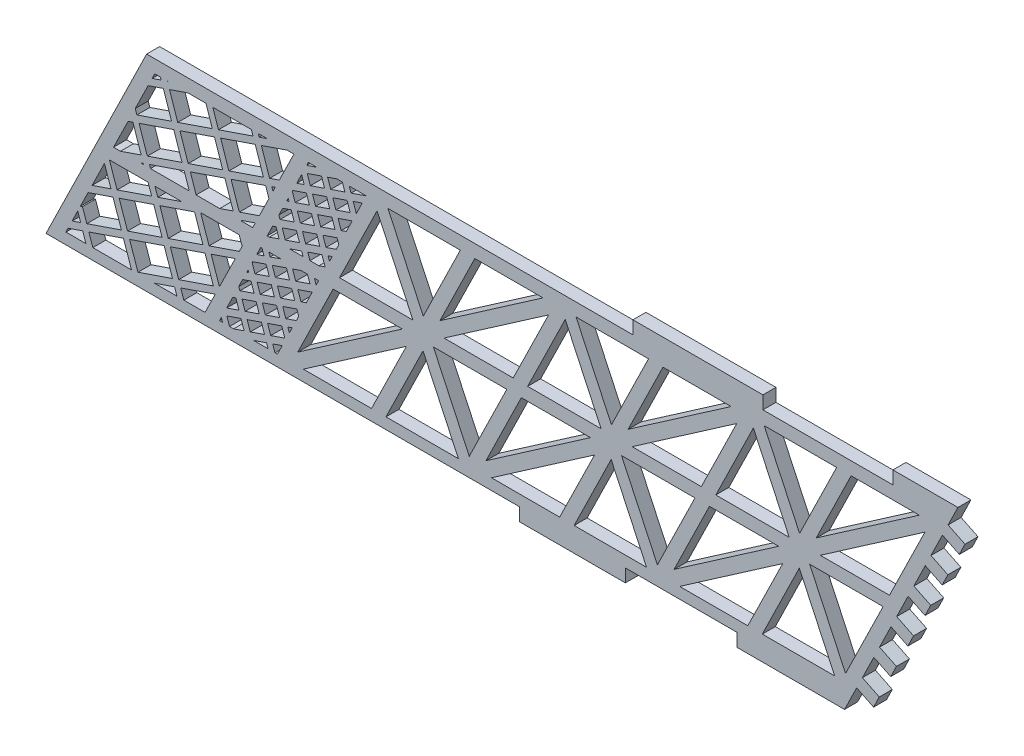
SolidWorks part; units mm, degrees
ref_plane "Front Plane" through (0, 0, 0) normal (0, 0, 1) x (1, 0, 0)
ref_plane "Top Plane" through (0, 0, 0) normal (0, 1, 0) x (1, 0, 0)
ref_plane "Right Plane" through (0, 0, 0) normal (1, 0, 0) x (0, 0, -1)
sketch "Sketch1" plane through (0, 0, 0) normal (0, 0, 1) x (1, 0, 0)
  line L3478 (51.1715, 290.0859) -> (43.1947, 287.3513)
  line L3479 (43.1947, 287.3513) -> (41.8771, 291.1947)
  line L3480 (41.8771, 291.1947) -> (50.7914, 291.1947)
  line L3481 (50.7914, 291.1947) -> (51.1715, 290.0859)
  line L3482 (51.658, 288.6669) -> (43.6811, 285.9324)
  line L3483 (43.6811, 285.9324) -> (45.6023, 280.3279)
  line L3484 (45.6023, 280.3279) -> (53.5792, 283.0625)
  line L3485 (53.5792, 283.0625) -> (51.658, 288.6669)
  line L3486 (55.4846, 282.13) -> (56.3022, 282.4102)
  line L3487 (56.3022, 282.4102) -> (55.7649, 281.3124)
  line L3488 (55.7649, 281.3124) -> (55.4846, 282.13)
  line L3489 (54.9982, 283.5489) -> (57.2347, 284.3156)
  line L3490 (57.2347, 284.3156) -> (60.6014, 291.1947)
  line L3491 (60.6014, 291.1947) -> (59.0316, 291.1947)
  line L3492 (59.0316, 291.1947) -> (53.0769, 289.1534)
  line L3493 (53.0769, 289.1534) -> (54.9982, 283.5489)
  line L3494 (52.5905, 290.5723) -> (54.406, 291.1947)
  line L3495 (54.406, 291.1947) -> (52.3771, 291.1947)
  line L3496 (52.3771, 291.1947) -> (52.5905, 290.5723)
  line L3497 (46.0888, 278.909) -> (48.01, 273.3046)
  line L3498 (48.01, 273.3046) -> (52.6189, 274.8845)
  line L3499 (52.6189, 274.8845) -> (54.8323, 279.407)
  line L3500 (54.8323, 279.407) -> (54.0656, 281.6436)
  line L3501 (54.0656, 281.6436) -> (46.0888, 278.909)
  line L3502 (22.1987, 256.6075) -> (30.1756, 259.342)
  line L3503 (30.1756, 259.342) -> (28.2543, 264.9465)
  line L3504 (28.2543, 264.9465) -> (20.2774, 262.2119)
  line L3505 (20.2774, 262.2119) -> (22.1987, 256.6075)
  line L3506 (19.791, 263.6308) -> (27.7679, 266.3654)
  line L3507 (27.7679, 266.3654) -> (26.9509, 268.7488)
  line L3508 (26.9509, 268.7488) -> (18.0365, 268.7488)
  line L3509 (18.0365, 268.7488) -> (19.791, 263.6308)
  line L3510 (18.3721, 263.1444) -> (14.0328, 261.6569)
  line L3511 (14.0328, 261.6569) -> (16.8845, 267.4837)
  line L3512 (16.8845, 267.4837) -> (18.3721, 263.1444)
  line L3513 (18.8585, 261.7255) -> (20.7797, 256.121)
  line L3514 (20.7797, 256.121) -> (12.8029, 253.3865)
  line L3515 (12.8029, 253.3865) -> (11.8034, 256.302)
  line L3516 (11.8034, 256.302) -> (11.3331, 256.1408)
  line L3517 (11.3331, 256.1408) -> (13.1003, 259.7515)
  line L3518 (13.1003, 259.7515) -> (18.8585, 261.7255)
  line L3519 (13.2893, 251.9675) -> (14.2028, 249.3028)
  line L3520 (14.2028, 249.3028) -> (23.1171, 249.3028)
  line L3521 (23.1171, 249.3028) -> (21.2662, 254.7021)
  line L3522 (21.2662, 254.7021) -> (13.2893, 251.9675)
  line L3523 (24.6064, 249.5841) -> (32.5833, 252.3186)
  line L3524 (32.5833, 252.3186) -> (30.662, 257.9231)
  line L3525 (30.662, 257.9231) -> (22.6851, 255.1885)
  line L3526 (22.6851, 255.1885) -> (24.6064, 249.5841)
  line L3527 (25.8466, 271.9698) -> (25.2017, 271.7488)
  line L3528 (25.2017, 271.7488) -> (25.9224, 271.7488)
  line L3529 (25.9224, 271.7488) -> (25.8466, 271.9698)
  line L3530 (23.439, 278.9932) -> (22.3317, 278.6137)
  line L3531 (22.3317, 278.6137) -> (18.9719, 271.7488)
  line L3532 (18.9719, 271.7488) -> (20.5761, 271.7488)
  line L3533 (20.5761, 271.7488) -> (25.3602, 273.3888)
  line L3534 (25.3602, 273.3888) -> (23.439, 278.9932)
  line L3535 (26.7792, 273.8752) -> (34.7876, 276.6206)
  line L3536 (34.7876, 276.6206) -> (32.8663, 282.225)
  line L3537 (32.8663, 282.225) -> (24.8579, 279.4797)
  line L3538 (24.8579, 279.4797) -> (26.7792, 273.8752)
  line L3539 (27.5081, 271.7488) -> (36.4577, 271.7488)
  line L3540 (36.4577, 271.7488) -> (35.274, 275.2016)
  line L3541 (35.274, 275.2016) -> (27.2656, 272.4563)
  line L3542 (27.2656, 272.4563) -> (27.5081, 271.7488)
  line L3543 (29.1868, 266.8518) -> (34.7204, 268.7488)
  line L3544 (34.7204, 268.7488) -> (28.5365, 268.7488)
  line L3545 (28.5365, 268.7488) -> (29.1868, 266.8518)
  line L3546 (31.5945, 259.8284) -> (39.6029, 262.5738)
  line L3547 (39.6029, 262.5738) -> (37.6817, 268.1782)
  line L3548 (37.6817, 268.1782) -> (29.6733, 265.4329)
  line L3549 (29.6733, 265.4329) -> (31.5945, 259.8284)
  line L3550 (34.0022, 252.805) -> (42.0106, 255.5504)
  line L3551 (42.0106, 255.5504) -> (40.0893, 261.1548)
  line L3552 (40.0893, 261.1548) -> (32.0809, 258.4095)
  line L3553 (32.0809, 258.4095) -> (34.0022, 252.805)
  line L3554 (24.3715, 280.8986) -> (32.3799, 283.644)
  line L3555 (32.3799, 283.644) -> (30.4586, 289.2484)
  line L3556 (30.4586, 289.2484) -> (26.9474, 288.0447)
  line L3557 (26.9474, 288.0447) -> (23.9919, 282.0059)
  line L3558 (23.9919, 282.0059) -> (24.3715, 280.8986)
  line L3559 (44.6698, 278.4226) -> (36.6929, 275.688)
  line L3560 (36.6929, 275.688) -> (38.0434, 271.7488)
  line L3561 (38.0434, 271.7488) -> (43.4716, 271.7488)
  line L3562 (43.4716, 271.7488) -> (46.5911, 272.8181)
  line L3563 (46.5911, 272.8181) -> (44.6698, 278.4226)
  line L3564 (42.2621, 285.446) -> (34.2853, 282.7114)
  line L3565 (34.2853, 282.7114) -> (36.2065, 277.107)
  line L3566 (36.2065, 277.107) -> (44.1834, 279.8415)
  line L3567 (44.1834, 279.8415) -> (42.2621, 285.446)
  line L3568 (41.7757, 286.8649) -> (33.7988, 284.1304)
  line L3569 (33.7988, 284.1304) -> (31.8776, 289.7348)
  line L3570 (31.8776, 289.7348) -> (36.1361, 291.1947)
  line L3571 (36.1361, 291.1947) -> (40.2914, 291.1947)
  line L3572 (40.2914, 291.1947) -> (41.7757, 286.8649)
  line L3573 (48.5434, 271.7488) -> (51.0843, 271.7488)
  line L3574 (51.0843, 271.7488) -> (51.6864, 272.9792)
  line L3575 (51.6864, 272.9792) -> (48.4964, 271.8856)
  line L3576 (48.4964, 271.8856) -> (48.5434, 271.7488)
  line L3577 (49.5718, 268.7488) -> (49.616, 268.7488)
  line L3578 (49.616, 268.7488) -> (49.59, 268.6956)
  line L3579 (49.59, 268.6956) -> (49.5718, 268.7488)
  line L3580 (29.9722, 290.6674) -> (27.8799, 289.9501)
  line L3581 (27.8799, 289.9501) -> (28.489, 291.1947)
  line L3582 (28.489, 291.1947) -> (29.7914, 291.1947)
  line L3583 (29.7914, 291.1947) -> (29.9722, 290.6674)
  line L3584 (31.3912, 291.1538) -> (31.5105, 291.1947)
  line L3585 (31.5105, 291.1947) -> (31.3771, 291.1947)
  line L3586 (31.3771, 291.1947) -> (31.3912, 291.1538)
  line L3587 (39.346, 268.7488) -> (39.1006, 268.6646)
  line L3588 (39.1006, 268.6646) -> (41.0219, 263.0602)
  line L3589 (41.0219, 263.0602) -> (48.0032, 265.4535)
  line L3590 (48.0032, 265.4535) -> (48.6575, 266.7903)
  line L3591 (48.6575, 266.7903) -> (47.9861, 268.7488)
  line L3592 (47.9861, 268.7488) -> (39.346, 268.7488)
  line L3593 (41.5083, 261.6413) -> (47.0707, 263.5481)
  line L3594 (47.0707, 263.5481) -> (43.4151, 256.0788)
  line L3595 (43.4151, 256.0788) -> (41.5083, 261.6413)
  line L3596 (33.0697, 250.8997) -> (33.6171, 249.3028)
  line L3597 (33.6171, 249.3028) -> (28.4116, 249.3028)
  line L3598 (28.4116, 249.3028) -> (33.0697, 250.8997)
  line L3599 (40.0989, 249.3028) -> (42.455, 254.117)
  line L3600 (42.455, 254.117) -> (34.4886, 251.3861)
  line L3601 (34.4886, 251.3861) -> (35.2028, 249.3028)
  line L3602 (35.2028, 249.3028) -> (40.0989, 249.3028)
  line L3603 (9.417, 252.2258) -> (11.3839, 252.9001)
  line L3604 (11.3839, 252.9001) -> (10.7097, 254.8669)
  line L3605 (10.7097, 254.8669) -> (9.417, 252.2258)
  line L3606 (11.8703, 251.4811) -> (12.6171, 249.3028)
  line L3607 (12.6171, 249.3028) -> (7.9865, 249.3028)
  line L3608 (7.9865, 249.3028) -> (8.4845, 250.3204)
  line L3609 (8.4845, 250.3204) -> (11.8703, 251.4811)
  line L3610 (70.7822, 283.4497) -> (71.4996, 281.357)
  line L3611 (71.4996, 281.357) -> (72.6858, 281.7636)
  line L3612 (72.6858, 281.7636) -> (74.0611, 284.5738)
  line L3613 (74.0611, 284.5738) -> (70.7822, 283.4497)
  line L3614 (72.8573, 288.0855) -> (69.5783, 286.9614)
  line L3615 (69.5783, 286.9614) -> (70.2957, 284.8687)
  line L3616 (70.2957, 284.8687) -> (73.5747, 285.9927)
  line L3617 (73.5747, 285.9927) -> (72.8573, 288.0855)
  line L3618 (72.3709, 289.5044) -> (69.0919, 288.3804)
  line L3619 (69.0919, 288.3804) -> (68.3745, 290.4731)
  line L3620 (68.3745, 290.4731) -> (70.4793, 291.1947)
  line L3621 (70.4793, 291.1947) -> (71.7914, 291.1947)
  line L3622 (71.7914, 291.1947) -> (72.3709, 289.5044)
  line L3623 (73.7898, 289.9908) -> (77.3015, 291.1947)
  line L3624 (77.3015, 291.1947) -> (73.3771, 291.1947)
  line L3625 (73.3771, 291.1947) -> (73.7898, 289.9908)
  line L3626 (74.9937, 286.4791) -> (76.369, 289.2893)
  line L3627 (76.369, 289.2893) -> (74.2762, 288.5719)
  line L3628 (74.2762, 288.5719) -> (74.9937, 286.4791)
  line L3629 (88.0737, 271.7488) -> (79.7946, 289.4641)
  line L3630 (79.7946, 289.4641) -> (71.1244, 271.7488)
  line L3631 (71.1244, 271.7488) -> (88.0737, 271.7488)
  line L3632 (70.5671, 279.4516) -> (67.2881, 278.3275)
  line L3633 (67.2881, 278.3275) -> (68.0055, 276.2348)
  line L3634 (68.0055, 276.2348) -> (70.3779, 277.0481)
  line L3635 (70.3779, 277.0481) -> (70.9737, 278.2654)
  line L3636 (70.9737, 278.2654) -> (70.5671, 279.4516)
  line L3637 (69.3632, 282.9633) -> (66.0843, 281.8392)
  line L3638 (66.0843, 281.8392) -> (66.8017, 279.7465)
  line L3639 (66.8017, 279.7465) -> (70.0806, 280.8705)
  line L3640 (70.0806, 280.8705) -> (69.3632, 282.9633)
  line L3641 (68.1594, 286.475) -> (64.8804, 285.3509)
  line L3642 (64.8804, 285.3509) -> (65.5978, 283.2582)
  line L3643 (65.5978, 283.2582) -> (68.8768, 284.3822)
  line L3644 (68.8768, 284.3822) -> (68.1594, 286.475)
  line L3645 (66.9555, 289.9867) -> (63.6766, 288.8626)
  line L3646 (63.6766, 288.8626) -> (64.394, 286.7699)
  line L3647 (64.394, 286.7699) -> (67.673, 287.8939)
  line L3648 (67.673, 287.8939) -> (66.9555, 289.9867)
  line L3649 (67.073, 274.3294) -> (63.794, 273.2054)
  line L3650 (63.794, 273.2054) -> (64.2934, 271.7488)
  line L3651 (64.2934, 271.7488) -> (66.3671, 271.7488)
  line L3652 (66.3671, 271.7488) -> (67.7904, 272.2367)
  line L3653 (67.7904, 272.2367) -> (67.073, 274.3294)
  line L3654 (65.8691, 277.8411) -> (62.5902, 276.7171)
  line L3655 (62.5902, 276.7171) -> (63.3076, 274.6243)
  line L3656 (63.3076, 274.6243) -> (66.5866, 275.7484)
  line L3657 (66.5866, 275.7484) -> (65.8691, 277.8411)
  line L3658 (64.6653, 281.3528) -> (61.3863, 280.2288)
  line L3659 (61.3863, 280.2288) -> (62.1038, 278.136)
  line L3660 (62.1038, 278.136) -> (65.3827, 279.2601)
  line L3661 (65.3827, 279.2601) -> (64.6653, 281.3528)
  line L3662 (63.4615, 284.8645) -> (60.3155, 283.7861)
  line L3663 (60.3155, 283.7861) -> (60.2281, 283.6074)
  line L3664 (60.2281, 283.6074) -> (60.8999, 281.6477)
  line L3665 (60.8999, 281.6477) -> (64.1789, 282.7718)
  line L3666 (64.1789, 282.7718) -> (63.4615, 284.8645)
  line L3667 (62.383, 288.0105) -> (61.248, 285.6914)
  line L3668 (61.248, 285.6914) -> (62.975, 286.2835)
  line L3669 (62.975, 286.2835) -> (62.383, 288.0105)
  line L3670 (68.8188, 273.8624) -> (69.4454, 275.1427)
  line L3671 (69.4454, 275.1427) -> (68.4919, 274.8158)
  line L3672 (68.4919, 274.8158) -> (68.8188, 273.8624)
  line L3673 (85.6238, 268.7488) -> (69.6561, 268.7488)
  line L3674 (69.6561, 268.7488) -> (61.4881, 252.0594)
  line L3675 (61.4881, 252.0594) -> (85.6238, 268.7488)
  line L3676 (64.7828, 265.6955) -> (61.5038, 264.5715)
  line L3677 (61.5038, 264.5715) -> (62.2212, 262.4787)
  line L3678 (62.2212, 262.4787) -> (63.4544, 262.9015)
  line L3679 (63.4544, 262.9015) -> (64.7988, 265.6486)
  line L3680 (64.7988, 265.6486) -> (64.7828, 265.6955)
  line L3681 (63.7361, 268.7488) -> (62.2415, 268.7488)
  line L3682 (62.2415, 268.7488) -> (60.2999, 268.0832)
  line L3683 (60.2999, 268.0832) -> (61.0174, 265.9904)
  line L3684 (61.0174, 265.9904) -> (64.2963, 267.1145)
  line L3685 (64.2963, 267.1145) -> (63.7361, 268.7488)
  line L3686 (62.3751, 272.7189) -> (59.545, 271.7488)
  line L3687 (59.545, 271.7488) -> (62.7077, 271.7488)
  line L3688 (62.7077, 271.7488) -> (62.3751, 272.7189)
  line L3689 (61.1712, 276.2306) -> (57.8923, 275.1066)
  line L3690 (57.8923, 275.1066) -> (58.6097, 273.0138)
  line L3691 (58.6097, 273.0138) -> (61.8887, 274.1379)
  line L3692 (61.8887, 274.1379) -> (61.1712, 276.2306)
  line L3693 (59.9674, 279.7423) -> (58.0077, 279.0705)
  line L3694 (58.0077, 279.0705) -> (57.1407, 277.299)
  line L3695 (57.1407, 277.299) -> (57.4058, 276.5255)
  line L3696 (57.4058, 276.5255) -> (60.6848, 277.6496)
  line L3697 (60.6848, 277.6496) -> (59.9674, 279.7423)
  line L3698 (59.2956, 281.7021) -> (58.9402, 280.9759)
  line L3699 (58.9402, 280.9759) -> (59.481, 281.1613)
  line L3700 (59.481, 281.1613) -> (59.2956, 281.7021)
  line L3701 (65.7153, 267.6009) -> (65.7622, 267.617)
  line L3702 (65.7622, 267.617) -> (66.3161, 268.7488)
  line L3703 (66.3161, 268.7488) -> (65.3218, 268.7488)
  line L3704 (65.3218, 268.7488) -> (65.7153, 267.6009)
  line L3705 (61.2887, 260.5734) -> (58.0097, 259.4493)
  line L3706 (58.0097, 259.4493) -> (58.7271, 257.3565)
  line L3707 (58.7271, 257.3565) -> (61.1465, 258.1859)
  line L3708 (61.1465, 258.1859) -> (61.7114, 259.3402)
  line L3709 (61.7114, 259.3402) -> (61.2887, 260.5734)
  line L3710 (60.0848, 264.0851) -> (56.8059, 262.961)
  line L3711 (56.8059, 262.961) -> (57.5233, 260.8682)
  line L3712 (57.5233, 260.8682) -> (60.8023, 261.9923)
  line L3713 (60.8023, 261.9923) -> (60.0848, 264.0851)
  line L3714 (58.881, 267.5968) -> (55.602, 266.4727)
  line L3715 (55.602, 266.4727) -> (56.3194, 264.3799)
  line L3716 (56.3194, 264.3799) -> (59.5984, 265.504)
  line L3717 (59.5984, 265.504) -> (58.881, 267.5968)
  line L3718 (56.4733, 274.6202) -> (55.6998, 274.355)
  line L3719 (55.6998, 274.355) -> (54.4243, 271.7488)
  line L3720 (54.4243, 271.7488) -> (54.9194, 271.7488)
  line L3721 (54.9194, 271.7488) -> (57.1907, 272.5274)
  line L3722 (57.1907, 272.5274) -> (56.4733, 274.6202)
  line L3723 (57.7946, 255.4512) -> (54.5156, 254.3271)
  line L3724 (54.5156, 254.3271) -> (55.233, 252.2344)
  line L3725 (55.233, 252.2344) -> (58.512, 253.3584)
  line L3726 (58.512, 253.3584) -> (57.7946, 255.4512)
  line L3727 (56.5908, 258.9629) -> (53.3118, 257.8388)
  line L3728 (53.3118, 257.8388) -> (54.0292, 255.7461)
  line L3729 (54.0292, 255.7461) -> (57.3082, 256.8701)
  line L3730 (57.3082, 256.8701) -> (56.5908, 258.9629)
  line L3731 (55.3869, 262.4746) -> (52.108, 261.3505)
  line L3732 (52.108, 261.3505) -> (52.8254, 259.2578)
  line L3733 (52.8254, 259.2578) -> (56.1043, 260.3818)
  line L3734 (56.1043, 260.3818) -> (55.3869, 262.4746)
  line L3735 (54.1831, 265.9863) -> (51.0841, 264.9239)
  line L3736 (51.0841, 264.9239) -> (50.9658, 264.6822)
  line L3737 (50.9658, 264.6822) -> (51.6215, 262.7695)
  line L3738 (51.6215, 262.7695) -> (54.9005, 263.8935)
  line L3739 (54.9005, 263.8935) -> (54.1831, 265.9863)
  line L3740 (53.2361, 268.7488) -> (52.956, 268.7488)
  line L3741 (52.956, 268.7488) -> (52.0166, 266.8293)
  line L3742 (52.0166, 266.8293) -> (53.6967, 267.4052)
  line L3743 (53.6967, 267.4052) -> (53.2361, 268.7488)
  line L3744 (55.1156, 267.8916) -> (57.6159, 268.7488)
  line L3745 (57.6159, 268.7488) -> (54.8218, 268.7488)
  line L3746 (54.8218, 268.7488) -> (55.1156, 267.8916)
  line L3747 (59.5565, 254.9372) -> (60.214, 256.2806)
  line L3748 (60.214, 256.2806) -> (59.2135, 255.9376)
  line L3749 (59.2135, 255.9376) -> (59.5565, 254.9372)
  line L3750 (54.3005, 250.329) -> (51.3071, 249.3028)
  line L3751 (51.3071, 249.3028) -> (54.6523, 249.3028)
  line L3752 (54.6523, 249.3028) -> (54.3005, 250.329)
  line L3753 (53.0967, 253.8407) -> (49.8177, 252.7166)
  line L3754 (49.8177, 252.7166) -> (50.5351, 250.6239)
  line L3755 (50.5351, 250.6239) -> (53.8141, 251.7479)
  line L3756 (53.8141, 251.7479) -> (53.0967, 253.8407)
  line L3757 (51.8929, 257.3524) -> (48.6139, 256.2283)
  line L3758 (48.6139, 256.2283) -> (49.3313, 254.1356)
  line L3759 (49.3313, 254.1356) -> (52.6103, 255.2596)
  line L3760 (52.6103, 255.2596) -> (51.8929, 257.3524)
  line L3761 (50.689, 260.8641) -> (48.7762, 260.2084)
  line L3762 (48.7762, 260.2084) -> (47.8784, 258.3739)
  line L3763 (47.8784, 258.3739) -> (48.1275, 257.6473)
  line L3764 (48.1275, 257.6473) -> (51.4064, 258.7713)
  line L3765 (51.4064, 258.7713) -> (50.689, 260.8641)
  line L3766 (50.0333, 262.7769) -> (49.7087, 262.1137)
  line L3767 (49.7087, 262.1137) -> (50.2026, 262.283)
  line L3768 (50.2026, 262.283) -> (50.0333, 262.7769)
  line L3769 (56.799, 249.3028) -> (57.9061, 251.565)
  line L3770 (57.9061, 251.565) -> (55.7195, 250.8154)
  line L3771 (55.7195, 250.8154) -> (56.238, 249.3028)
  line L3772 (56.238, 249.3028) -> (56.799, 249.3028)
  line L3773 (48.3988, 252.2302) -> (45.1198, 251.1062)
  line L3774 (45.1198, 251.1062) -> (45.738, 249.3028)
  line L3775 (45.738, 249.3028) -> (46.6815, 249.3028)
  line L3776 (46.6815, 249.3028) -> (49.1162, 250.1375)
  line L3777 (49.1162, 250.1375) -> (48.3988, 252.2302)
  line L3778 (47.1949, 255.7419) -> (46.4684, 255.4928)
  line L3779 (46.4684, 255.4928) -> (45.093, 252.6827)
  line L3780 (45.093, 252.6827) -> (47.9124, 253.6492)
  line L3781 (47.9124, 253.6492) -> (47.1949, 255.7419)
  line L3782 (43.8584, 250.1601) -> (44.1523, 249.3028)
  line L3783 (44.1523, 249.3028) -> (43.4389, 249.3028)
  line L3784 (43.4389, 249.3028) -> (43.8584, 250.1601)
  line L3785 (63.5559, 290.407) -> (63.9414, 291.1947)
  line L3786 (63.9414, 291.1947) -> (65.8538, 291.1947)
  line L3787 (65.8538, 291.1947) -> (63.5559, 290.407)
  line L3788 (181.1444, 274.7508) -> (189.1923, 291.1947)
  line L3789 (189.1923, 291.1947) -> (204.925, 291.1947)
  line L3790 (204.925, 291.1947) -> (181.1444, 274.7508)
  line L3791 (182.0776, 271.7488) -> (198.0453, 271.7488)
  line L3792 (198.0453, 271.7488) -> (206.2133, 288.4381)
  line L3793 (206.2133, 288.4381) -> (182.0776, 271.7488)
  line L3794 (156.4967, 268.7488) -> (148.3287, 252.0594)
  line L3795 (148.3287, 252.0594) -> (172.4644, 268.7488)
  line L3796 (172.4644, 268.7488) -> (156.4967, 268.7488)
  line L3797 (165.3497, 249.3028) -> (173.3976, 265.7467)
  line L3798 (173.3976, 265.7467) -> (149.617, 249.3028)
  line L3799 (149.617, 249.3028) -> (165.3497, 249.3028)
  line L3800 (154.625, 271.7488) -> (162.793, 288.4381)
  line L3801 (162.793, 288.4381) -> (138.6573, 271.7488)
  line L3802 (138.6573, 271.7488) -> (154.625, 271.7488)
  line L3803 (145.772, 291.1947) -> (137.7241, 274.7508)
  line L3804 (137.7241, 274.7508) -> (161.5047, 291.1947)
  line L3805 (161.5047, 291.1947) -> (145.772, 291.1947)
  line L3806 (113.0764, 268.7488) -> (104.9084, 252.0594)
  line L3807 (104.9084, 252.0594) -> (129.0441, 268.7488)
  line L3808 (129.0441, 268.7488) -> (113.0764, 268.7488)
  line L3809 (121.9294, 249.3028) -> (129.9773, 265.7467)
  line L3810 (129.9773, 265.7467) -> (106.1967, 249.3028)
  line L3811 (106.1967, 249.3028) -> (121.9294, 249.3028)
  line L3812 (111.2047, 271.7488) -> (119.3727, 288.4381)
  line L3813 (119.3727, 288.4381) -> (95.237, 271.7488)
  line L3814 (95.237, 271.7488) -> (111.2047, 271.7488)
  line L3815 (102.3517, 291.1947) -> (94.3038, 274.7508)
  line L3816 (94.3038, 274.7508) -> (118.0844, 291.1947)
  line L3817 (118.0844, 291.1947) -> (102.3517, 291.1947)
  line L3818 (98.5635, 249.3028) -> (90.3992, 266.7727)
  line L3819 (90.3992, 266.7727) -> (81.8491, 249.3028)
  line L3820 (81.8491, 249.3028) -> (98.5635, 249.3028)
  line L3821 (179.6277, 268.7488) -> (196.577, 268.7488)
  line L3822 (196.577, 268.7488) -> (187.9068, 251.0334)
  line L3823 (187.9068, 251.0334) -> (179.6277, 268.7488)
  line L3824 (166.6352, 289.4641) -> (157.965, 271.7488)
  line L3825 (157.965, 271.7488) -> (174.9143, 271.7488)
  line L3826 (174.9143, 271.7488) -> (166.6352, 289.4641)
  line L3827 (177.2398, 266.7727) -> (168.6897, 249.3028)
  line L3828 (168.6897, 249.3028) -> (185.4041, 249.3028)
  line L3829 (185.4041, 249.3028) -> (177.2398, 266.7727)
  line L3830 (177.3022, 273.7248) -> (185.8523, 291.1947)
  line L3831 (185.8523, 291.1947) -> (169.1379, 291.1947)
  line L3832 (169.1379, 291.1947) -> (177.3022, 273.7248)
  line L3833 (144.4865, 251.0334) -> (153.1567, 268.7488)
  line L3834 (153.1567, 268.7488) -> (136.2074, 268.7488)
  line L3835 (136.2074, 268.7488) -> (144.4865, 251.0334)
  line L3836 (133.8195, 266.7727) -> (125.2694, 249.3028)
  line L3837 (125.2694, 249.3028) -> (141.9838, 249.3028)
  line L3838 (141.9838, 249.3028) -> (133.8195, 266.7727)
  line L3839 (123.2149, 289.4641) -> (114.5447, 271.7488)
  line L3840 (114.5447, 271.7488) -> (131.494, 271.7488)
  line L3841 (131.494, 271.7488) -> (123.2149, 289.4641)
  line L3842 (133.8819, 273.7248) -> (142.432, 291.1947)
  line L3843 (142.432, 291.1947) -> (125.7176, 291.1947)
  line L3844 (125.7176, 291.1947) -> (133.8819, 273.7248)
  line L3845 (101.0662, 251.0334) -> (109.7364, 268.7488)
  line L3846 (109.7364, 268.7488) -> (92.7871, 268.7488)
  line L3847 (92.7871, 268.7488) -> (101.0662, 251.0334)
  line L3848 (90.4616, 273.7248) -> (99.0117, 291.1947)
  line L3849 (99.0117, 291.1947) -> (82.2973, 291.1947)
  line L3850 (82.2973, 291.1947) -> (90.4616, 273.7248)
  line L3851 (78.5091, 249.3028) -> (86.557, 265.7467)
  line L3852 (86.557, 265.7467) -> (62.7764, 249.3028)
  line L3853 (62.7764, 249.3028) -> (78.5091, 249.3028)
  line L3854 (211.5725, 292.5638) -> (215.4717, 290.6555)
  line L3855 (215.4717, 290.6555) -> (214.1529, 287.9609)
  line L3856 (214.1529, 287.9609) -> (210.2537, 289.8692)
  line L3857 (210.2537, 289.8692) -> (207.6162, 284.48)
  line L3858 (207.6162, 284.48) -> (211.5154, 282.5717)
  line L3859 (211.5154, 282.5717) -> (210.1966, 279.8771)
  line L3860 (210.1966, 279.8771) -> (206.2974, 281.7854)
  line L3861 (206.2974, 281.7854) -> (203.6598, 276.3962)
  line L3862 (203.6598, 276.3962) -> (207.559, 274.4879)
  line L3863 (207.559, 274.4879) -> (206.2403, 271.7933)
  line L3864 (206.2403, 271.7933) -> (202.3411, 273.7017)
  line L3865 (202.3411, 273.7017) -> (199.7035, 268.3125)
  line L3866 (199.7035, 268.3125) -> (203.6027, 266.4041)
  line L3867 (203.6027, 266.4041) -> (202.2839, 263.7095)
  line L3868 (202.2839, 263.7095) -> (198.3847, 265.6179)
  line L3869 (198.3847, 265.6179) -> (195.7472, 260.2287)
  line L3870 (195.7472, 260.2287) -> (199.6464, 258.3204)
  line L3871 (199.6464, 258.3204) -> (198.3276, 255.6258)
  line L3872 (198.3276, 255.6258) -> (194.4284, 257.5341)
  line L3873 (194.4284, 257.5341) -> (191.7908, 252.1449)
  line L3874 (191.7908, 252.1449) -> (195.6901, 250.2366)
  line L3875 (195.6901, 250.2366) -> (194.3713, 247.542)
  line L3876 (194.3713, 247.542) -> (190.4721, 249.4503)
  line L3877 (190.4721, 249.4503) -> (187.6761, 243.7376)
  line L3878 (187.6761, 243.7376) -> (162.8944, 243.7376)
  line L3879 (162.8944, 243.7376) -> (162.8944, 246.7376)
  line L3880 (162.8944, 246.7376) -> (137.0944, 246.7376)
  line L3881 (137.0944, 246.7376) -> (137.0944, 243.7376)
  line L3882 (137.0944, 243.7376) -> (112.6444, 243.7376)
  line L3883 (112.6444, 243.7376) -> (112.6444, 246.7376)
  line L3884 (112.6444, 246.7376) -> (3.391, 246.7376)
  line L3885 (3.391, 246.7376) -> (26.6173, 294.1947)
  line L3886 (26.6173, 294.1947) -> (138.8389, 294.1947)
  line L3887 (138.8389, 294.1947) -> (138.8389, 297.1947)
  line L3888 (138.8389, 297.1947) -> (168.8389, 297.1947)
  line L3889 (168.8389, 297.1947) -> (168.8389, 294.1947)
  line L3890 (168.8389, 294.1947) -> (198.8389, 294.1947)
  line L3891 (198.8389, 294.1947) -> (198.8389, 297.1947)
  line L3892 (198.8389, 297.1947) -> (213.8389, 297.1947)
  line L3893 (213.8389, 297.1947) -> (211.5725, 292.5638)
extrude "Boss-Extrude1" add sketch "Sketch1" along normal blind 3
